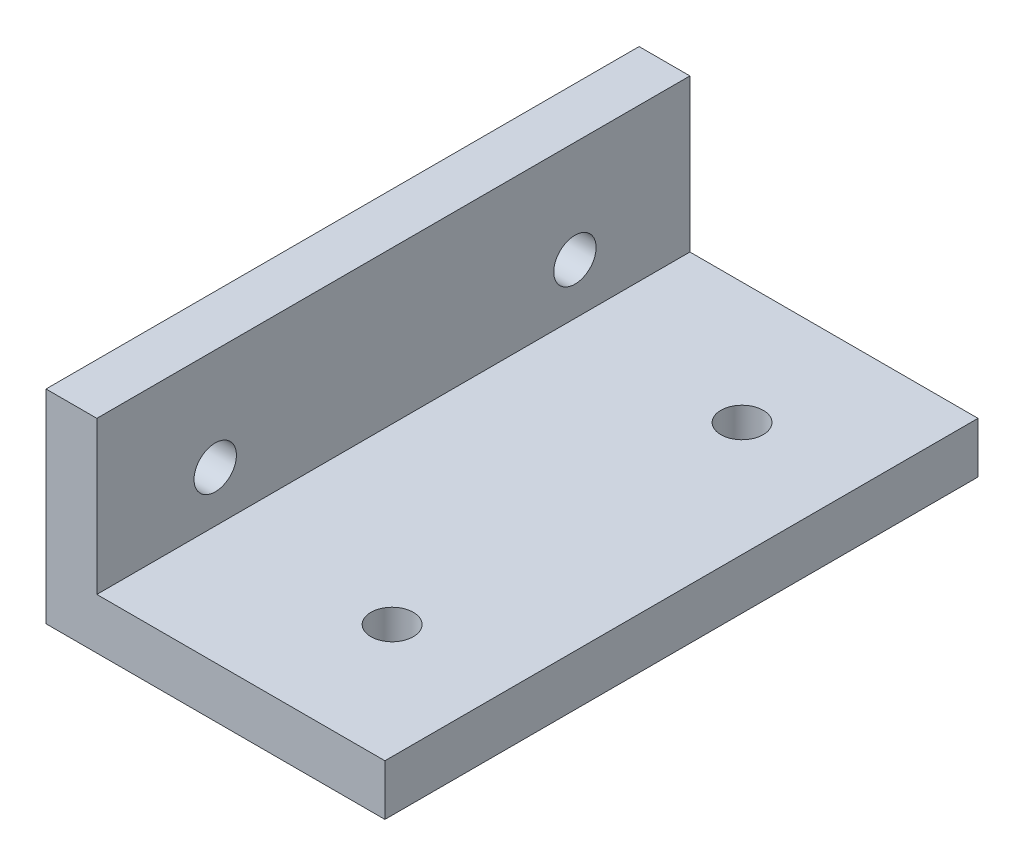
SolidWorks part; units mm, degrees
material "3.0205 (EN AW-1200)"
ref_plane "Plan de face" through (0, 0, 0) normal (0, 0, 1) x (1, 0, 0)
ref_plane "Plan de dessus" through (0, 0, 0) normal (0, 1, 0) x (1, 0, 0)
ref_plane "Plan de droite" through (0, 0, 0) normal (1, 0, 0) x (0, 0, -1)
sketch "Esquisse1" plane through (0, 0, 0) normal (0, 0, 1) x (1, 0, 0)
  line L0 (0, 0) -> (0, 12)
  line L1 (0, 12) -> (3, 12)
  line L2 (3, 12) -> (3, 3)
  line L3 (3, 3) -> (20, 3)
  line L4 (20, 3) -> (20, 0)
  line L5 (20, 0) -> (0, 0)
  dimension "D1" = 12
  dimension "D2" = 20
  dimension "D3" = 3
  dimension "D4" = 3
extrude "Boss.-Extru.1" add sketch "Esquisse1" along normal blind 35
hole_wizard "Trou taraudé M31" positions "Esquisse3" profile "Esquisse2" tap size "M3" standard "ISO"
sketch "Esquisse3" plane through (0, 3, 0) normal (0, 1, 0) x (-1, 0, 0)
  point P1 (-13.25, 27.8246)
  point P4 (-13.25, 7.1754)
sketch "Esquisse2" plane through (13.25, 3, 27.8246) normal (1, 0, 0) x (0, 0, 1)
  line L0 (0, 0) -> (0, 5.6511)
  line L1 (0, 5.6511) -> (1.25, 4.9)
  line L2 (1.25, 4.9) -> (1.25, 0)
  line L5 (1.25, 0) -> (0, 0)
  line L10 (0, 5.6511) -> (-1.25, 4.9) construction
  line L11 (0, -6.35) -> (0, 107.95) construction
  dimension "Diamètre du trou pour taraudage" = 2.5
  dimension "Profondeur du trou pour taraudage" = 4.9
  dimension "Angle de pointe" = 118
cosmetic thread "Filetage de perçage1" parameters "D1"=2.4, "D2"=3
cosmetic thread "Filetage de perçage2" parameters "D1"=2.4, "D2"=3
hole_wizard "Trou taraudé M32" positions "Esquisse5" profile "Esquisse4" tap size "M3" standard "ISO"
sketch "Esquisse5" plane through (0, 0, 0) normal (-1, 0, 0) x (0, 0, 1)
  point P1 (6.7868, 6)
  point P4 (28.0132, 6)
sketch "Esquisse4" plane through (0, 6, 6.7868) normal (0, 1, 0) x (0, 0, 1)
  line L0 (0, 0) -> (0, 5.6511)
  line L1 (0, 5.6511) -> (1.25, 4.9)
  line L2 (1.25, 4.9) -> (1.25, 0)
  line L5 (1.25, 0) -> (0, 0)
  line L10 (0, 5.6511) -> (-1.25, 4.9) construction
  line L11 (0, -6.35) -> (0, 107.95) construction
  dimension "Diamètre du trou pour taraudage" = 2.5
  dimension "Profondeur du trou pour taraudage" = 4.9
  dimension "Angle de pointe" = 118
cosmetic thread "Filetage de perçage4" parameters "D1"=2.4, "D2"=3
cosmetic thread "Filetage de perçage5" parameters "D1"=2.4, "D2"=3
